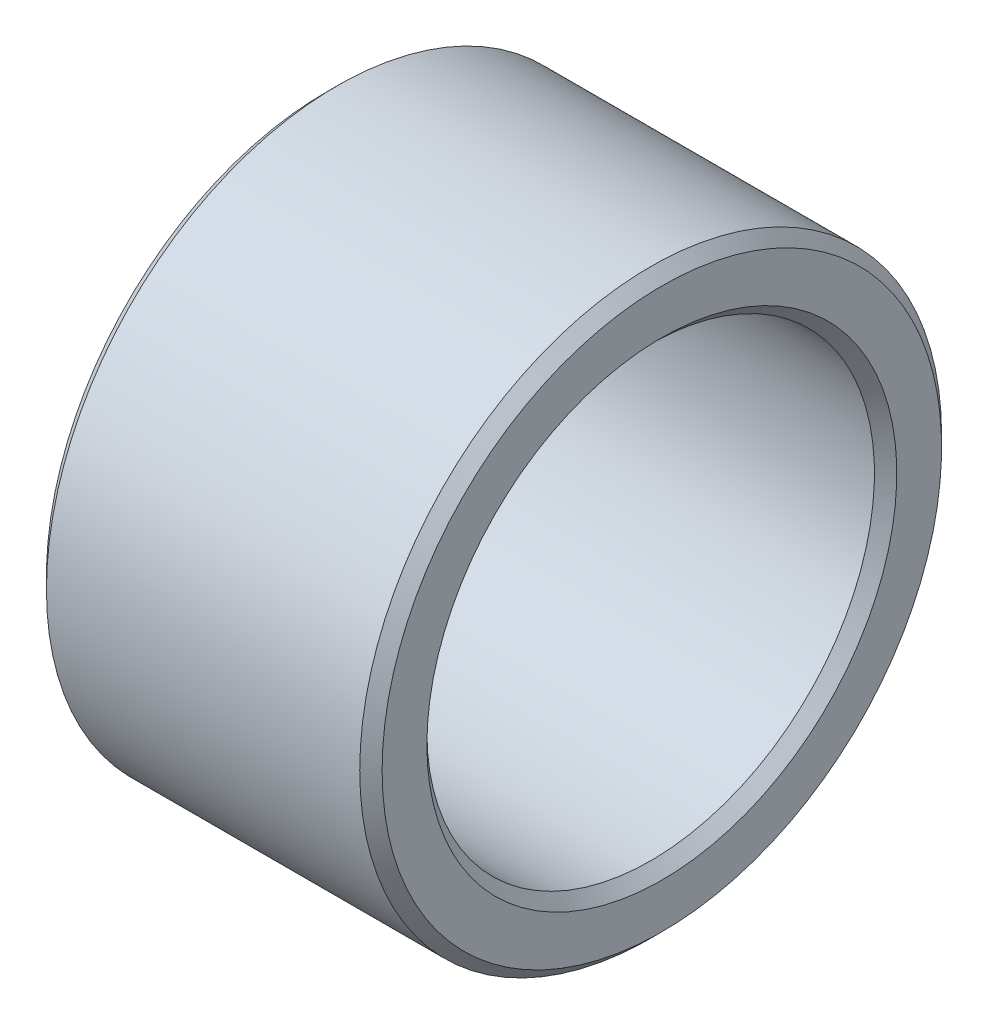
SolidWorks part; units mm, degrees
ref_plane "Přední rovina" through (0, 0, 0) normal (0, 0, 1) x (1, 0, 0)
ref_plane "Vrchní rovina" through (0, 0, 0) normal (0, 1, 0) x (1, 0, 0)
ref_plane "Pravá rovina" through (0, 0, 0) normal (1, 0, 0) x (0, 0, -1)
sketch "Skica1" plane through (0, 0, 0) normal (0, 0, 1) x (1, 0, 0)
  line L0 (0, 13) -> (15, 13)
  line L1 (15, 13) -> (15, 10)
  line L2 (15, 10) -> (0, 10)
  line L3 (0, 10) -> (0, 13)
  line L4 (0, 0) -> (15, 0) construction
  dimension "L" = 15
  dimension "d_" = 20
  dimension "D" = 26
revolve "Otočit kolem osy1" add sketch "Skica1" angle 360 about L4
chamfer "Zkosit1" distance 0.5 angle 45 4 edges at (0, 0, 10) (15, 0, 10) (15, 0, 13) (0, 0, 13)
